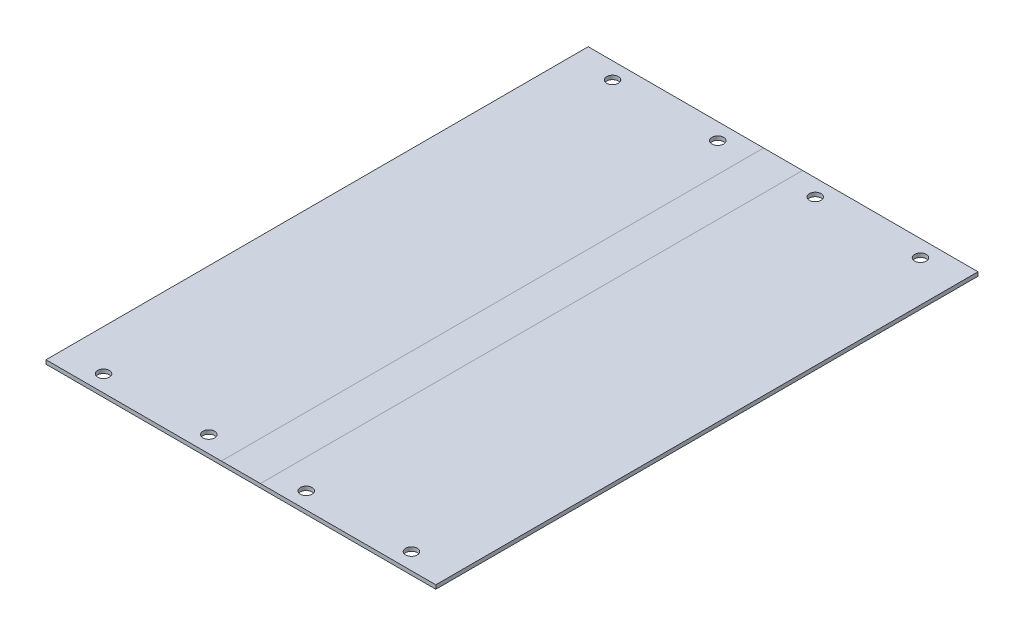
SolidWorks part; units mm, degrees
ref_plane "前基準面" through (0, 0, 0) normal (0, 0, 1) x (1, 0, 0)
ref_plane "上基準面" through (0, 0, 0) normal (0, 1, 0) x (1, 0, 0)
ref_plane "右基準面" through (0, 0, 0) normal (1, 0, 0) x (0, 0, -1)
sketch "草圖1" plane through (0, 0, 0) normal (0, 1, 0) x (1, 0, 0)
  line L1 (-50, 69.55) -> (50, 69.55)
  line L2 (-50, 69.55) -> (-50, -69.55)
  line L3 (-50, -69.55) -> (50, -69.55)
  line L4 (50, 69.55) -> (50, -69.55)
  line L5 (-50, 69.55) -> (50, -69.55) construction
  line L6 (-50, -69.55) -> (50, 69.55) construction
  point P0 (0, 0)
  dimension "D1" = 100
  dimension "D2" = 139.1
extrude "填料-伸長1" add sketch "草圖1" along normal blind 1
sketch "草圖2" plane through (0, 1, 0) normal (0, 1, 0) x (1, 0, 0)
  line L0 (0, 69.55) -> (0, -69.55) construction
  line L1 (50, 69.55) -> (-50, 69.55) construction
  line L2 (-50, -69.55) -> (50, -69.55) construction
  line L3 (-50, 65.29) -> (50, 65.29) construction
  line L4 (-50, 69.55) -> (-50, -69.55) construction
  line L5 (50, -69.55) -> (50, 69.55) construction
  line L6 (-50, 0) -> (50, 0) construction
  circle A0 centre (-12.5, 65.29) radius 1.5
  circle A1 centre (-39.5, 65.29) radius 1.5
  circle A2 centre (39.5, 65.29) radius 1.5
  circle A3 centre (12.5, 65.29) radius 1.5
  circle A4 centre (39.5, -65.29) radius 1.5
  circle A5 centre (12.5, -65.29) radius 1.5
  circle A6 centre (-12.5, -65.29) radius 1.5
  circle A7 centre (-39.5, -65.29) radius 1.5
  dimension "D3" = 3
  dimension "D4" = 3
  dimension "D1" = 4.26
  dimension "D2" = 12.5
  dimension "D5" = 27
extrude "除料-伸長1" cut sketch "草圖2" against normal blind 1
sketch "草圖3" plane through (0, 1, 0) normal (0, 1, 0) x (1, 0, 0)
  line L0 (0, 69.55) -> (0, -69.55) construction
  line L1 (50, 69.55) -> (-50, 69.55) construction
  line L2 (-50, -69.55) -> (50, -69.55) construction
  line L3 (-5, 69.55) -> (-5, -69.55)
  line L4 (5, 69.55) -> (5, -69.55)
  dimension "D1" = 10
  dimension "D2" = 5
split line "分割線1"
